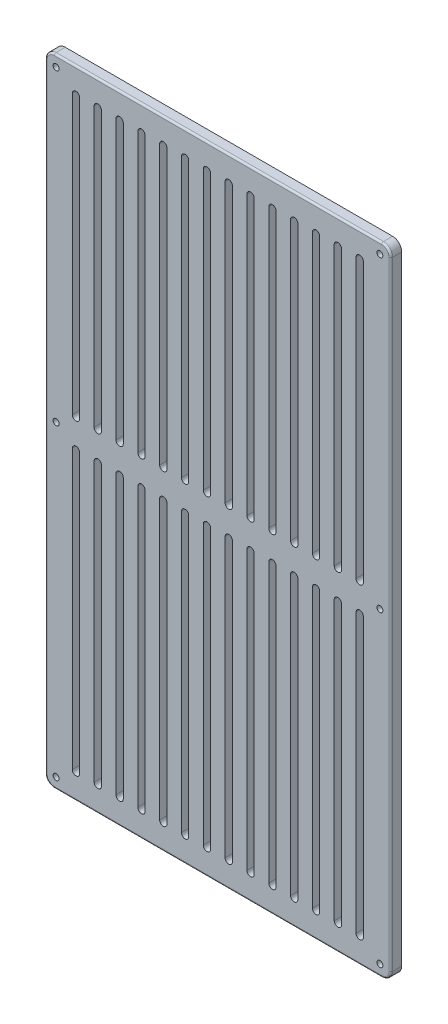
SolidWorks part; units mm, degrees
ref_plane "Front Plane" through (0, 0, 0) normal (0, 0, 1) x (1, 0, 0)
ref_plane "Top Plane" through (0, 0, 0) normal (0, 1, 0) x (1, 0, 0)
ref_plane "Right Plane" through (0, 0, 0) normal (1, 0, 0) x (0, 0, -1)
sketch "Sketch1" plane through (0, 0, 0) normal (0, 0, 1) x (1, 0, 0)
  line B0 (1, 6) -> (1, 346)
  line B1 (123.9021, 337) -> (123.9021, 184)
  line B2 (6, 351) -> (186, 351)
  arc B3 (55.9021, 337) -> (51.9021, 337) centre (53.9021, 337) ccw
  line B4 (55.9021, 337) -> (55.9021, 184)
  line B5 (51.9021, 337) -> (51.9021, 184)
  line B6 (191, 346) -> (191, 6)
  line B7 (175.9021, 337) -> (175.9021, 184)
  line B8 (171.9021, 337) -> (171.9021, 184)
  line B9 (163.9021, 337) -> (163.9021, 184)
  line B10 (159.9021, 337) -> (159.9021, 184)
  line B11 (151.9021, 337) -> (151.9021, 184)
  line B12 (147.9021, 337) -> (147.9021, 184)
  line B13 (139.9021, 337) -> (139.9021, 184)
  line B14 (135.9021, 337) -> (135.9021, 184)
  line B15 (115.9021, 337) -> (115.9021, 184)
  line B16 (99.9021, 337) -> (99.9021, 184)
  line B17 (91.9021, 337) -> (91.9021, 184)
  line B18 (79.9021, 337) -> (79.9021, 184)
  line B19 (63.9021, 337) -> (63.9021, 184)
  line B20 (43.9021, 337) -> (43.9021, 184)
  line B21 (39.9021, 337) -> (39.9021, 184)
  line B22 (19.9021, 337) -> (19.9021, 184)
  line B23 (15.9021, 337) -> (15.9021, 184)
  line B24 (27.9021, 337) -> (27.9021, 184)
  line B25 (67.9021, 337) -> (67.9021, 184)
  line B26 (75.9021, 337) -> (75.9021, 184)
  line B27 (87.9021, 337) -> (87.9021, 184)
  line B28 (103.9021, 337) -> (103.9021, 184)
  line B29 (111.9021, 337) -> (111.9021, 184)
  line B30 (31.9021, 337) -> (31.9021, 184)
  circle B31 centre (7, 345) radius 1.65
  circle B32 centre (185, 345) radius 1.65
  circle B33 centre (7, 7) radius 1.65
  circle B34 centre (185, 7) radius 1.65
  circle B35 centre (7, 176) radius 1.65
  circle B36 centre (185, 176) radius 1.65
  line B37 (6, 1) -> (186, 1)
  arc B38 (1, 6) -> (6, 1) centre (6, 6) ccw
  arc B39 (6, 351) -> (1, 346) centre (6, 346) ccw
  arc B40 (191, 346) -> (186, 351) centre (186, 346) ccw
  arc B41 (186, 1) -> (191, 6) centre (186, 6) ccw
  arc B42 (15.9021, 184) -> (19.9021, 184) centre (17.9021, 184) ccw
  arc B43 (19.9021, 337) -> (15.9021, 337) centre (17.9021, 337) ccw
  arc B44 (31.9021, 337) -> (27.9021, 337) centre (29.9021, 337) ccw
  arc B45 (27.9021, 184) -> (31.9021, 184) centre (29.9021, 184) ccw
  arc B46 (43.9021, 337) -> (39.9021, 337) centre (41.9021, 337) ccw
  arc B47 (39.9021, 184) -> (43.9021, 184) centre (41.9021, 184) ccw
  arc B48 (51.9021, 184) -> (55.9021, 184) centre (53.9021, 184) ccw
  arc B49 (67.9021, 337) -> (63.9021, 337) centre (65.9021, 337) ccw
  arc B50 (63.9021, 184) -> (67.9021, 184) centre (65.9021, 184) ccw
  arc B51 (79.9021, 337) -> (75.9021, 337) centre (77.9021, 337) ccw
  arc B52 (75.9021, 184) -> (79.9021, 184) centre (77.9021, 184) ccw
  arc B53 (91.9021, 337) -> (87.9021, 337) centre (89.9021, 337) ccw
  arc B54 (87.9021, 184) -> (91.9021, 184) centre (89.9021, 184) ccw
  arc B55 (103.9021, 337) -> (99.9021, 337) centre (101.9021, 337) ccw
  arc B56 (99.9021, 184) -> (103.9021, 184) centre (101.9021, 184) ccw
  arc B57 (115.9021, 337) -> (111.9021, 337) centre (113.9021, 337) ccw
  arc B58 (111.9021, 184) -> (115.9021, 184) centre (113.9021, 184) ccw
  arc B59 (127.9021, 337) -> (123.9021, 337) centre (125.9021, 337) ccw
  line B60 (127.9021, 337) -> (127.9021, 184)
  arc B61 (123.9021, 184) -> (127.9021, 184) centre (125.9021, 184) ccw
  arc B62 (139.9021, 337) -> (135.9021, 337) centre (137.9021, 337) ccw
  arc B63 (135.9021, 184) -> (139.9021, 184) centre (137.9021, 184) ccw
  arc B64 (151.9021, 337) -> (147.9021, 337) centre (149.9021, 337) ccw
  arc B65 (147.9021, 184) -> (151.9021, 184) centre (149.9021, 184) ccw
  arc B66 (163.9021, 337) -> (159.9021, 337) centre (161.9021, 337) ccw
  arc B67 (159.9021, 184) -> (163.9021, 184) centre (161.9021, 184) ccw
  arc B68 (175.9021, 337) -> (171.9021, 337) centre (173.9021, 337) ccw
  arc B69 (171.9021, 184) -> (175.9021, 184) centre (173.9021, 184) ccw
  line B70 (171.9021, 15) -> (171.9021, 168)
  arc B71 (175.9021, 168) -> (171.9021, 168) centre (173.9021, 168) ccw
  line B72 (175.9021, 15) -> (175.9021, 168)
  arc B73 (171.9021, 15) -> (175.9021, 15) centre (173.9021, 15) ccw
  line B74 (159.9021, 15) -> (159.9021, 168)
  arc B75 (163.9021, 168) -> (159.9021, 168) centre (161.9021, 168) ccw
  line B76 (163.9021, 15) -> (163.9021, 168)
  arc B77 (159.9021, 15) -> (163.9021, 15) centre (161.9021, 15) ccw
  line B78 (147.9021, 15) -> (147.9021, 168)
  arc B79 (151.9021, 168) -> (147.9021, 168) centre (149.9021, 168) ccw
  line B80 (151.9021, 15) -> (151.9021, 168)
  arc B81 (147.9021, 15) -> (151.9021, 15) centre (149.9021, 15) ccw
  line B82 (135.9021, 15) -> (135.9021, 168)
  arc B83 (139.9021, 168) -> (135.9021, 168) centre (137.9021, 168) ccw
  line B84 (139.9021, 15) -> (139.9021, 168)
  arc B85 (135.9021, 15) -> (139.9021, 15) centre (137.9021, 15) ccw
  line B86 (123.9021, 15) -> (123.9021, 168)
  arc B87 (127.9021, 168) -> (123.9021, 168) centre (125.9021, 168) ccw
  line B88 (127.9021, 15) -> (127.9021, 168)
  arc B89 (123.9021, 15) -> (127.9021, 15) centre (125.9021, 15) ccw
  line B90 (111.9021, 15) -> (111.9021, 168)
  arc B91 (115.9021, 168) -> (111.9021, 168) centre (113.9021, 168) ccw
  line B92 (115.9021, 15) -> (115.9021, 168)
  arc B93 (111.9021, 15) -> (115.9021, 15) centre (113.9021, 15) ccw
  line B94 (99.9021, 15) -> (99.9021, 168)
  arc B95 (103.9021, 168) -> (99.9021, 168) centre (101.9021, 168) ccw
  line B96 (103.9021, 15) -> (103.9021, 168)
  arc B97 (99.9021, 15) -> (103.9021, 15) centre (101.9021, 15) ccw
  line B98 (87.9021, 15) -> (87.9021, 168)
  arc B99 (91.9021, 168) -> (87.9021, 168) centre (89.9021, 168) ccw
  line B100 (91.9021, 15) -> (91.9021, 168)
  arc B101 (87.9021, 15) -> (91.9021, 15) centre (89.9021, 15) ccw
  line B102 (75.9021, 15) -> (75.9021, 168)
  arc B103 (79.9021, 168) -> (75.9021, 168) centre (77.9021, 168) ccw
  line B104 (79.9021, 15) -> (79.9021, 168)
  arc B105 (75.9021, 15) -> (79.9021, 15) centre (77.9021, 15) ccw
  line B106 (63.9021, 15) -> (63.9021, 168)
  arc B107 (67.9021, 168) -> (63.9021, 168) centre (65.9021, 168) ccw
  line B108 (67.9021, 15) -> (67.9021, 168)
  arc B109 (63.9021, 15) -> (67.9021, 15) centre (65.9021, 15) ccw
  line B110 (51.9021, 15) -> (51.9021, 168)
  arc B111 (55.9021, 168) -> (51.9021, 168) centre (53.9021, 168) ccw
  line B112 (55.9021, 15) -> (55.9021, 168)
  arc B113 (51.9021, 15) -> (55.9021, 15) centre (53.9021, 15) ccw
  line B114 (39.9021, 15) -> (39.9021, 168)
  arc B115 (43.9021, 168) -> (39.9021, 168) centre (41.9021, 168) ccw
  line B116 (43.9021, 15) -> (43.9021, 168)
  arc B117 (39.9021, 15) -> (43.9021, 15) centre (41.9021, 15) ccw
  line B118 (27.9021, 15) -> (27.9021, 168)
  arc B119 (31.9021, 168) -> (27.9021, 168) centre (29.9021, 168) ccw
  line B120 (31.9021, 15) -> (31.9021, 168)
  arc B121 (27.9021, 15) -> (31.9021, 15) centre (29.9021, 15) ccw
  line B122 (19.9021, 15) -> (19.9021, 168)
  arc B123 (15.9021, 15) -> (19.9021, 15) centre (17.9021, 15) ccw
  line B124 (15.9021, 15) -> (15.9021, 168)
  arc B125 (19.9021, 168) -> (15.9021, 168) centre (17.9021, 168) ccw
sketch_block_instance "panel-1"
sketch_block "panel"
extrude "Boss-Extrude1" add sketch "Sketch1" along normal blind 6
chamfer "Chamfer1" distance 1.1 angle 45 6 edges at (186.65, 345, 0) (8.65, 7, 0) (186.65, 7, 0) (186.65, 176, 0) (8.65, 176, 0) (8.65, 345, 0)
fillet "Fillet1" radius 1 8 edges at (189.5355, 349.5355, 6) (191, 176, 6) (189.5355, 2.4645, 6) (96, 1, 6) (2.4645, 2.4645, 6) (1, 176, 6) (2.4645, 349.5355, 6) (96, 351, 6)
sketch "Sketch2" plane through (0, 0, 0) normal (0, 0, -1) x (-1, 0, 0)
  line L0 (-1, 346) -> (-1, 6) construction
  line L1 (-191, 351) -> (-1, 351)
  line L2 (-191, 351) -> (-191, 176)
  line L3 (-191, 176) -> (-1, 176)
  line L4 (-1, 351) -> (-1, 176)
  line L6 (-1, 176) -> (-191, 176)
  line L7 (-1, 176) -> (-1, 1)
  line L8 (-1, 1) -> (-191, 1)
  line L9 (-191, 176) -> (-191, 1)
